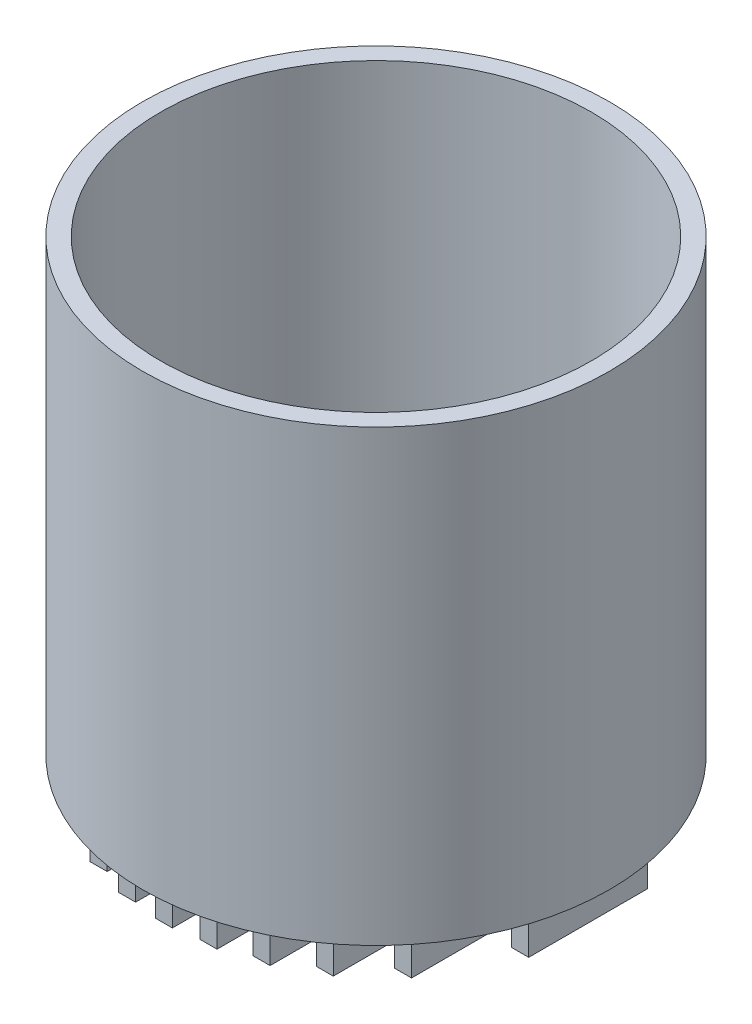
SolidWorks part; units mm, degrees
ref_plane "Front Plane" through (0, 0, 0) normal (0, 0, 1) x (1, 0, 0)
ref_plane "Top Plane" through (0, 0, 0) normal (0, 1, 0) x (1, 0, 0)
ref_plane "Right Plane" through (0, 0, 0) normal (1, 0, 0) x (0, 0, -1)
sketch "Sketch1" plane through (0, 0, 0) normal (0, 1, 0) x (1, 0, 0)
  circle A0 centre (0, 0) radius 38.1
  dimension "D1" = 76.2
extrude "Boss-Extrude1" add sketch "Sketch1" along normal blind 76.2
shell "Shell2" thickness 3.175
sketch "Sketch2" plane through (0, -3.175, 0) normal (0, -1, 0) x (1, 0, 0)
  line L0 (0, 0) -> (0, -37.5)
  line L1 (0, -37.5) -> (0, 37.5)
  line L4 (1.5, 37.5) -> (1.5, -37.5)
  line L5 (1.5, 37.5) -> (-1.5, 37.5)
  line L6 (1.5, -37.5) -> (-1.5, -37.5)
  line L7 (-1.5, 37.5) -> (-1.5, -37.5)
  line L8 (1.5, 37.5) -> (-1.5, -37.5) construction
  line L9 (1.5, -37.5) -> (-1.5, 37.5) construction
  line L10 (-1.5, 0) -> (-7.2, 0)
  line L11 (-5.7, 36.8023) -> (-5.7, -36.8023)
  line L12 (-5.7, 36.8023) -> (-8.7, 36.8023)
  line L13 (-5.7, -36.8023) -> (-8.7, -36.8023)
  line L14 (-8.7, 36.8023) -> (-8.7, -36.8023)
  line L15 (-5.7, 36.8023) -> (-8.7, -36.8023) construction
  line L16 (-5.7, -36.8023) -> (-8.7, 36.8023) construction
  line L17 (-7.2, 0) -> (-14.4, 0)
  line L18 (-12.9, 34.625) -> (-12.9, -34.625)
  line L19 (-12.9, 34.625) -> (-15.9, 34.625)
  line L20 (-12.9, -34.625) -> (-15.9, -34.625)
  line L21 (-15.9, 34.625) -> (-15.9, -34.625)
  line L22 (-12.9, 34.625) -> (-15.9, -34.625) construction
  line L23 (-12.9, -34.625) -> (-15.9, 34.625) construction
  line L24 (-14.4, 0) -> (-21.6, 0)
  line L25 (-20.1, 30.6544) -> (-20.1, -30.6544)
  line L26 (-20.1, 30.6544) -> (-23.1, 30.6544)
  line L27 (-20.1, -30.6544) -> (-23.1, -30.6544)
  line L28 (-23.1, 30.6544) -> (-23.1, -30.6544)
  line L29 (-20.1, 30.6544) -> (-23.1, -30.6544) construction
  line L30 (-20.1, -30.6544) -> (-23.1, 30.6544) construction
  line L31 (-21.6, 0) -> (-28.8, 0)
  line L32 (-27.3, 24.0169) -> (-27.3, -24.0169)
  line L33 (-27.3, 24.0169) -> (-30.3, 24.0169)
  line L34 (-27.3, -24.0169) -> (-30.3, -24.0169)
  line L35 (-30.3, 24.0169) -> (-30.3, -24.0169)
  line L36 (-27.3, 24.0169) -> (-30.3, -24.0169) construction
  line L37 (-27.3, -24.0169) -> (-30.3, 24.0169) construction
  line L38 (-28.8, 0) -> (-36, 0)
  line L39 (-34.5, 10.5) -> (-34.5, -10.5)
  line L40 (-34.5, 10.5) -> (-37.5, 10.5)
  line L41 (-34.5, -10.5) -> (-37.5, -10.5)
  line L42 (-37.5, 10.5) -> (-37.5, -10.5)
  line L43 (-34.5, 10.5) -> (-37.5, -10.5) construction
  line L44 (-34.5, -10.5) -> (-37.5, 10.5) construction
  line L45 (34.5, -10.5) -> (37.5, 10.5) construction
  line L46 (34.5, 10.5) -> (37.5, -10.5) construction
  line L47 (27.3, -24.0169) -> (30.3, 24.0169) construction
  line L48 (27.3, 24.0169) -> (30.3, -24.0169) construction
  line L49 (20.1, -30.6544) -> (23.1, 30.6544) construction
  line L50 (20.1, 30.6544) -> (23.1, -30.6544) construction
  line L51 (12.9, -34.625) -> (15.9, 34.625) construction
  line L52 (12.9, 34.625) -> (15.9, -34.625) construction
  line L53 (5.7, -36.8023) -> (8.7, 36.8023) construction
  line L54 (5.7, 36.8023) -> (8.7, -36.8023) construction
  line L55 (37.5, 10.5) -> (37.5, -10.5)
  line L56 (34.5, -10.5) -> (37.5, -10.5)
  line L57 (34.5, 10.5) -> (37.5, 10.5)
  line L58 (34.5, 10.5) -> (34.5, -10.5)
  line L59 (28.8, 0) -> (36, 0)
  line L60 (30.3, 24.0169) -> (30.3, -24.0169)
  line L61 (27.3, -24.0169) -> (30.3, -24.0169)
  line L62 (27.3, 24.0169) -> (30.3, 24.0169)
  line L63 (27.3, 24.0169) -> (27.3, -24.0169)
  line L64 (21.6, 0) -> (28.8, 0)
  line L65 (23.1, 30.6544) -> (23.1, -30.6544)
  line L66 (20.1, -30.6544) -> (23.1, -30.6544)
  line L67 (20.1, 30.6544) -> (23.1, 30.6544)
  line L68 (20.1, 30.6544) -> (20.1, -30.6544)
  line L69 (14.4, 0) -> (21.6, 0)
  line L70 (15.9, 34.625) -> (15.9, -34.625)
  line L71 (12.9, -34.625) -> (15.9, -34.625)
  line L72 (12.9, 34.625) -> (15.9, 34.625)
  line L73 (12.9, 34.625) -> (12.9, -34.625)
  line L74 (7.2, 0) -> (14.4, 0)
  line L75 (8.7, 36.8023) -> (8.7, -36.8023)
  line L76 (5.7, -36.8023) -> (8.7, -36.8023)
  line L77 (5.7, 36.8023) -> (8.7, 36.8023)
  line L78 (5.7, 36.8023) -> (5.7, -36.8023)
  dimension "D2" = 3
  dimension "D3" = 5.7
  dimension "D4" = 3
  dimension "D5" = 7.2
  dimension "D6" = 3
  dimension "D7" = 7.2
  dimension "D8" = 3
  dimension "D9" = 7.2
  dimension "D10" = 3
  dimension "D11" = 7.2
  dimension "D12" = 3
extrude "Boss-Extrude2" add sketch "Sketch2" along normal blind 7
scale "Scale1" scale about centroid uniform scaling yes scale factor 0.615385
